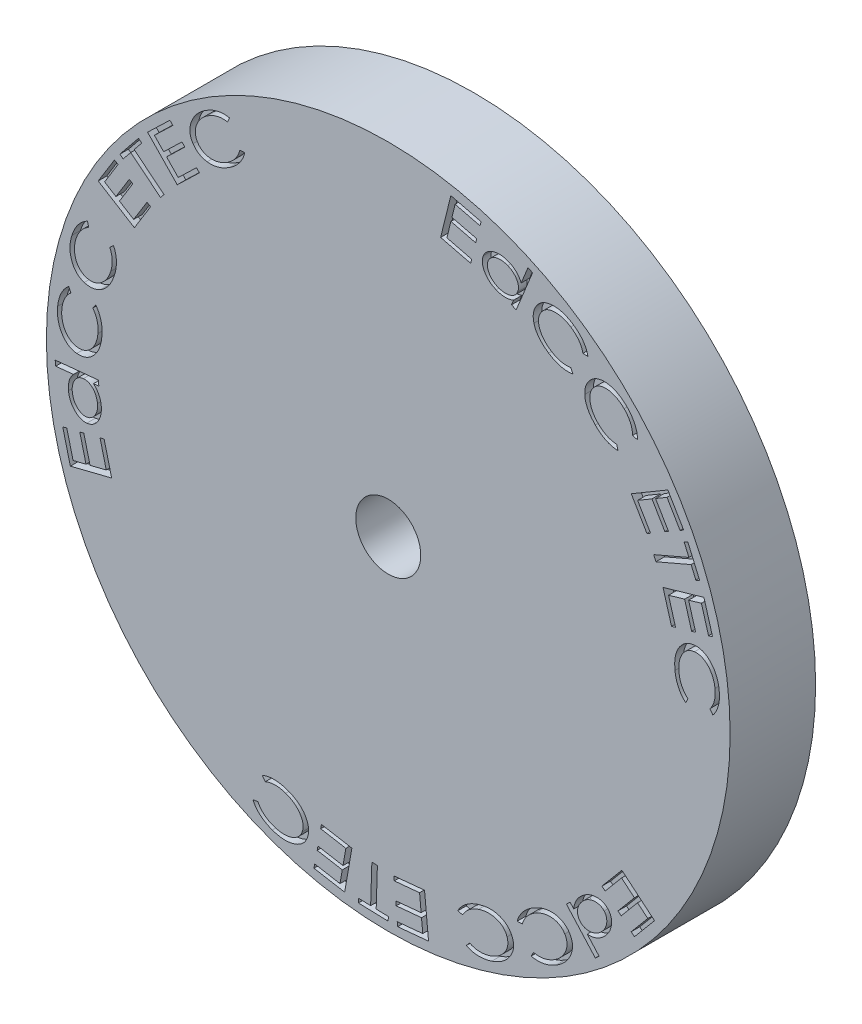
SolidWorks part; units mm, degrees
ref_plane "Front Plane" through (0, 0, 0) normal (0, 0, 1) x (1, 0, 0)
ref_plane "Top Plane" through (0, 0, 0) normal (0, 1, 0) x (1, 0, 0)
ref_plane "Right Plane" through (0, 0, 0) normal (1, 0, 0) x (0, 0, -1)
sketch "Sketch1" plane through (0, 0, 0) normal (0, 0, 1) x (1, 0, 0)
  circle A0 centre (0, 0) radius 3.8
  circle A1 centre (0, 0) radius 40
  dimension "D1" = 80
  dimension "D2" = 7.6
extrude "Boss-Extrude1" add sketch "Sketch1" along normal blind 10
sketch "Sketch2" plane through (0, 0, 0) normal (0, 0, -1) x (-1, 0, 0)
  circle A0 centre (0, 0) radius 8.8
  circle A1 centre (0, 0) radius 38
  circle A2 centre (0, 0) radius 40 construction
  circle A3 centre (0, 0) radius 3.8 construction
  dimension "D1" = 2
  dimension "D2" = 5
extrude "Cut-Extrude1" cut sketch "Sketch2" against normal blind 8
sketch "Sketch3" plane through (0, 0, 10) normal (0, 0, 1) x (1, 0, 0)
  circle A0 centre (0, 0) radius 34 construction
  text T0 "EdCC ETEC           EdCC ETEC         EdCC ETEC" font "Century Gothic" height 5
extrude "Cut-Extrude3" cut sketch "Sketch3" against normal blind 1
fillet "Fillet1" radius 5 2 edges at (-8.8, 0, 8) (-38, 0, 8)
